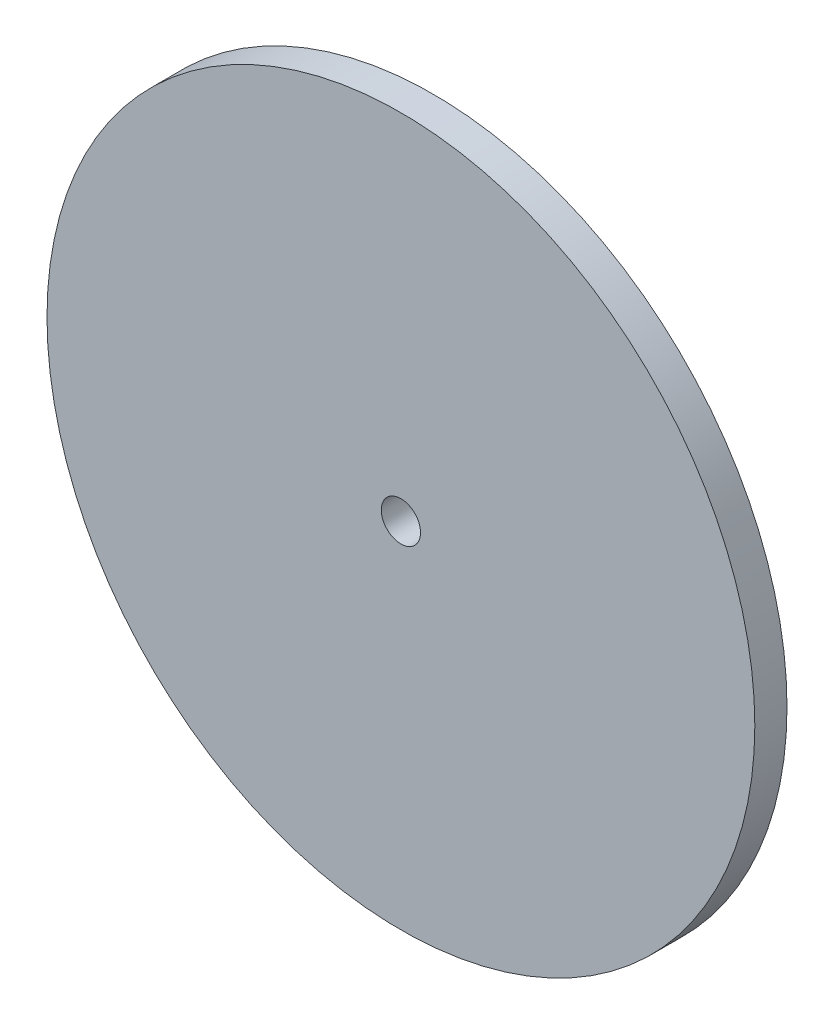
SolidWorks part; units mm, degrees
material "Maple"
ref_plane "前视基准面" through (0, 0, 0) normal (0, 0, 1) x (1, 0, 0)
ref_plane "上视基准面" through (0, 0, 0) normal (0, 1, 0) x (1, 0, 0)
ref_plane "右视基准面" through (0, 0, 0) normal (1, 0, 0) x (0, 0, -1)
sketch "草图1" plane through (0, 0, 0) normal (0, 0, 1) x (1, 0, 0)
  circle A0 centre (0, 0) radius 3.05
  circle A1 centre (0, 0) radius 55
extrude "凸台-拉伸1" add sketch "草图1" along normal blind 5
